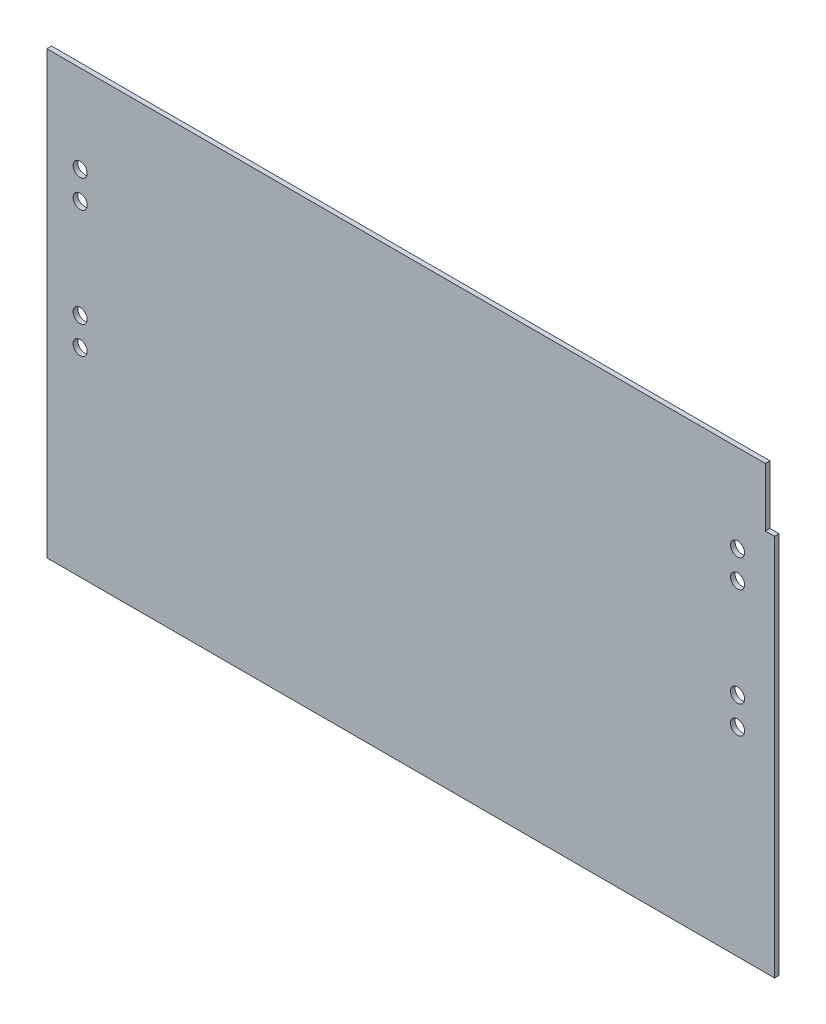
SolidWorks part; units mm, degrees
material "Pine"
ref_plane "Front Plane" through (0, 0, 0) normal (0, 0, 1) x (1, 0, 0)
ref_plane "Top Plane" through (0, 0, 0) normal (0, 1, 0) x (1, 0, 0)
ref_plane "Right Plane" through (0, 0, 0) normal (1, 0, 0) x (0, 0, -1)
sketch "Sketch1" plane through (0, 0, 0) normal (0, 0, 1) x (1, 0, 0)
  line L0 (-249.8725, -120.9675) -> (-249.8725, -151.4475)
  line L1 (-211.7725, -151.4475) -> (211.7725, -151.4475)
  line L2 (-249.8725, -120.9675) -> (-249.8725, 151.4475)
  line L3 (-249.8725, 151.4475) -> (243.5225, 151.4475)
  line L4 (249.8725, -120.9675) -> (249.8725, 111.2647)
  line L5 (-249.8725, -151.4475) -> (-211.7725, -151.4475)
  line L6 (211.7725, -151.4475) -> (249.8725, -151.4475)
  line L9 (249.8725, 111.2647) -> (243.5225, 111.2647)
  line L10 (243.5225, 151.4475) -> (243.5225, 111.2647)
  line L17 (249.8725, -151.4475) -> (249.8725, -120.9675)
  circle A0 centre (-227.0125, -14.9225) radius 4.826
  circle A1 centre (-227.0125, 4.1275) radius 4.826
  circle A2 centre (-227.0125, 91.1225) radius 4.826
  circle A3 centre (-227.0125, 72.0725) radius 4.826
  circle A4 centre (224.4725, -14.9225) radius 4.826
  circle A5 centre (224.4725, 4.1275) radius 4.826
  circle A6 centre (224.4725, 91.1225) radius 4.826
  circle A7 centre (224.4725, 72.0725) radius 4.826
  point P0 (0, 0)
  dimension "D6" = 9.652
  dimension "D7" = 22.86
  dimension "D8" = 9.652
  dimension "D10" = 60.325
  dimension "D16" = 136.525
  dimension "D1" = 136.525
  dimension "D3" = 40.1828
  dimension "D4" = 6.35
  dimension "D9" = 19.05
  dimension "D12" = 22.86
  dimension "D14" = 19.05
  dimension "D18" = 19.05
  dimension "D19" = 25.4
  dimension "D21" = 60.325
  dimension "D23" = 19.05
  dimension "D24" = 151.4475
extrude "Boss-Extrude1" add sketch "Sketch1" along normal blind 3.175
